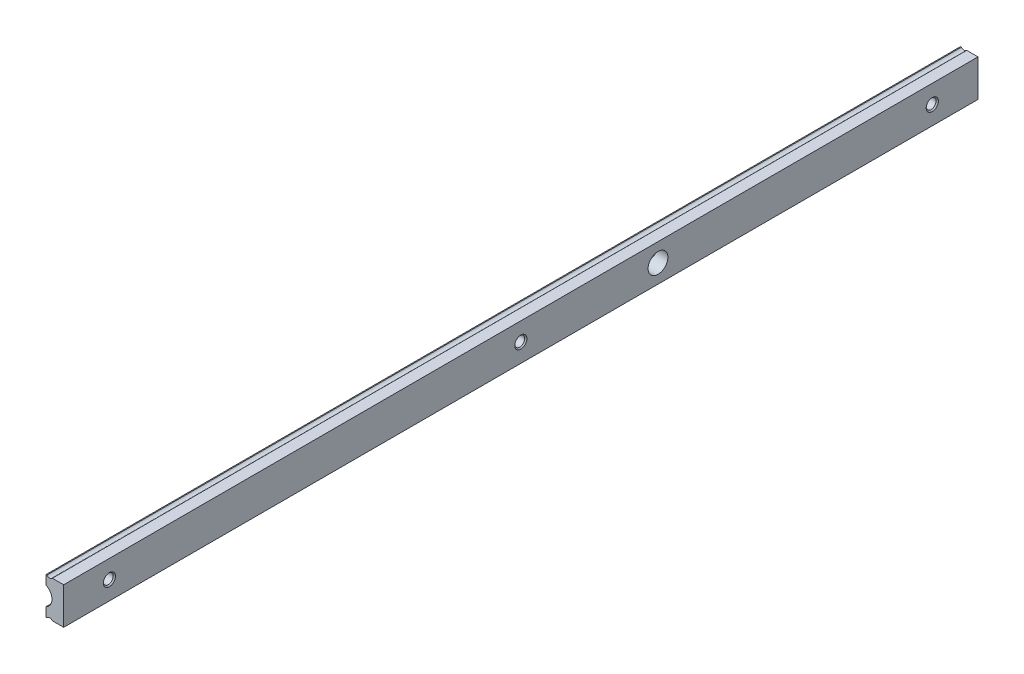
SolidWorks part; units mm, degrees
ref_plane "Front" through (0, 0, 0) normal (0, 0, 1) x (1, 0, 0)
ref_plane "Top" through (0, 0, 0) normal (0, 1, 0) x (1, 0, 0)
ref_plane "Right" through (0, 0, 0) normal (1, 0, 0) x (0, 0, -1)
ref_plane "Plane1" through (0, 0, 0) normal (0, 0, 1) x (1, 0, 0)
sketch "Sketch1" plane through (0, 0, 0) normal (0, 0, 1) x (1, 0, 0)
  line L0 (0, 2.9747) -> (0, 0)
  line L1 (0, 0) -> (0.3056, 0)
  line L2 (2.0944, 0) -> (5.8, 0)
  line L3 (5.8, 0) -> (5.8, 12.1)
  line L4 (5.8, 12.1) -> (2.0944, 12.1)
  line L5 (0.3056, 12.1) -> (0, 12.1)
  line L6 (0, 12.1) -> (0, 9.1253)
  arc A0 (0.3056, 0) -> (2.0944, 0) centre (1.2, -0.8) cw
  arc A1 (2.0944, 12.1) -> (0.3056, 12.1) centre (1.2, 12.9) cw
  arc A2 (0, 9.1253) -> (0, 2.9747) centre (-1.45, 6.05) cw
extrude "Boss-Extrude1" add sketch "Sketch1" along normal blind 300
ref_plane "Plane2" through (0, 0, 15) normal (0, 0, 1) x (1, 0, 0)
sketch "Sketch2" plane through (0, 0, 15) normal (0, 0, 1) x (1, 0, 0)
  line L0 (1.2995, 6.05) -> (1.2995, 8.05)
  line L1 (1.2995, 8.05) -> (1.6785, 7.671)
  line L2 (1.6785, 7.671) -> (5.421, 7.671)
  line L3 (5.421, 7.671) -> (5.8, 8.05)
  line L4 (5.8, 8.05) -> (5.8, 6.05)
  line L5 (5.8, 6.05) -> (1.2995, 6.05)
  line L6 (5.8, 6.05) -> (0, 6.05) construction
revolve "Cut-Revolve1" cut sketch "Sketch2" angle 360 about L6
cosmetic thread "Cosmetic Thread1" parameters "D1"=4.1215, "D2"=4
ref_plane "Plane3" through (0, 0, 285) normal (0, 0, 1) x (1, 0, 0)
sketch "Sketch3" plane through (0, 0, 285) normal (0, 0, 1) x (1, 0, 0)
  line L0 (1.2995, 6.05) -> (1.2995, 8.05)
  line L1 (1.2995, 8.05) -> (1.6785, 7.671)
  line L2 (1.6785, 7.671) -> (5.421, 7.671)
  line L3 (5.421, 7.671) -> (5.8, 8.05)
  line L4 (5.8, 8.05) -> (5.8, 6.05)
  line L5 (5.8, 6.05) -> (1.2995, 6.05)
  line L6 (5.8, 6.05) -> (0, 6.05) construction
revolve "Cut-Revolve2" cut sketch "Sketch3" angle 360 about L6
cosmetic thread "Cosmetic Thread2" parameters "D1"=4.1215, "D2"=4
ref_plane "Plane4" through (0, 0, 150) normal (0, 0, 1) x (1, 0, 0)
sketch "Sketch4" plane through (0, 0, 150) normal (0, 0, 1) x (1, 0, 0)
  line L0 (1.2995, 6.05) -> (1.2995, 8.05)
  line L1 (1.2995, 8.05) -> (1.6785, 7.671)
  line L2 (1.6785, 7.671) -> (5.421, 7.671)
  line L3 (5.421, 7.671) -> (5.8, 8.05)
  line L4 (5.8, 8.05) -> (5.8, 6.05)
  line L5 (5.8, 6.05) -> (1.2995, 6.05)
  line L6 (5.8, 6.05) -> (0, 6.05) construction
revolve "Cut-Revolve3" cut sketch "Sketch4" angle 360 about L6
cosmetic thread "Cosmetic Thread3" parameters "D1"=4.1215, "D2"=4
ref_plane "Plane5" through (5.8, 0, 0) normal (1, 0, 0) x (0, 0, -1)
sketch "Sketch5" plane through (5.8, 0, 0) normal (1, 0, 0) x (0, 0, -1)
  circle A0 centre (-105, 6.05) radius 3.25
extrude "Cut-Extrude1" cut sketch "Sketch5" against normal blind 6
